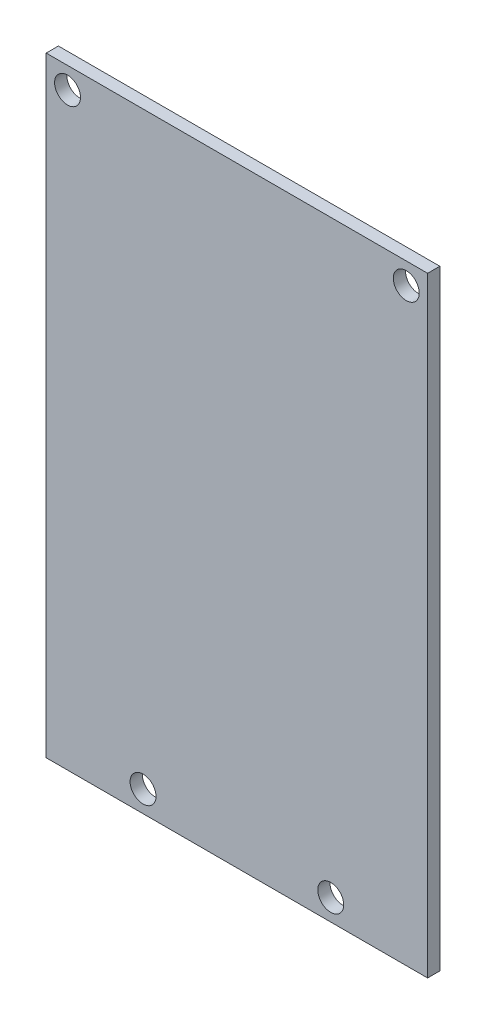
SolidWorks part; units mm, degrees
ref_plane "Plan de face" through (0, 0, 0) normal (0, 0, 1) x (1, 0, 0)
ref_plane "Plan de dessus" through (0, 0, 0) normal (0, 1, 0) x (1, 0, 0)
ref_plane "Plan de droite" through (0, 0, 0) normal (1, 0, 0) x (0, 0, -1)
sketch "Esquisse1" plane through (0, 0, 0) normal (0, 0, 1) x (1, 0, 0)
  line L1 (-25, 40) -> (25, 40)
  line L2 (-25, 40) -> (-25, -40)
  line L3 (-25, -40) -> (25, -40)
  line L4 (25, 40) -> (25, -40)
  line L5 (-25, 40) -> (25, -40) construction
  line L6 (-25, -40) -> (25, 40) construction
  point P0 (0, 0)
  dimension "D1" = 50
  dimension "D2" = 80
extrude "Boss.-Extru.1" add sketch "Esquisse1" along normal blind 1.6 contours L2 L3 L4 L1
hole_wizard "Dégagement M31" positions "Esquisse2" profile "Esquisse4" hole size "M3" standard "Ansi Metric" end condition through all
sketch "Esquisse2" plane through (0, 0, 1.6) normal (0, 0, 1) x (1, 0, 0)
  line L0 (-22.2, 37.2) -> (22.2, 37.2) construction
  line L2 (-25, 40) -> (25, 40) construction
  line L3 (22.2, 37.2) -> (25, 37.2) construction
  line L4 (25, 40) -> (25, -40) construction
  line L6 (22.2, 37.2) -> (22.2, 40) construction
  line L8 (-12.3, -37.2) -> (12.3, -37.2) construction
  line L10 (-25, -40) -> (25, -40) construction
  line L11 (-5.8338, -37.2) -> (-5.8338, -40) construction
  point P0 (-22.2, 37.2)
  point P2 (22.2, 37.2)
  point P4 (12.3, -37.2)
  point P6 (-12.3, -37.2)
  point P15 (0, 40)
  point P16 (0, 37.2)
  point P32 (0, -40)
  point P33 (0, -37.2)
  dimension "D1" = 44.4
  dimension "D2" = 24.6
  dimension "D3" = 2.8
sketch "Esquisse4" plane through (-22.2, 37.2, 1.6) normal (1, 0, 0) x (0, -1, 0)
  line L0 (0, 0) -> (0, 1.6)
  line L1 (0, 1.6) -> (1.7, 1.6)
  line L2 (1.7, 1.6) -> (1.7, 0)
  line L5 (1.7, 0) -> (0, 0)
  line L11 (0, -6.35) -> (0, 107.95) construction
  dimension "Diamètre du perçage jusqu'au prochain" = 3.4
  dimension "Profondeur du perçage jusqu'au prochain" = 1.6
